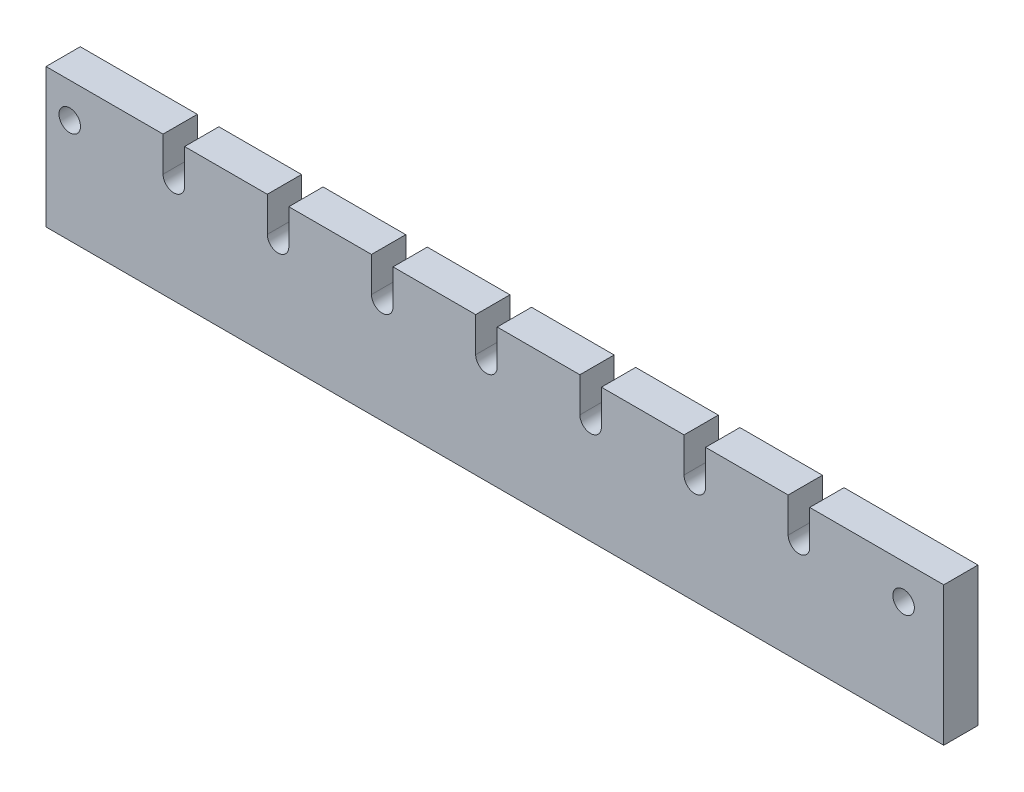
SolidWorks part; units mm, degrees
ref_plane "Front Plane" through (0, 0, 0) normal (0, 0, 1) x (1, 0, 0)
ref_plane "Top Plane" through (0, 0, 0) normal (0, 1, 0) x (1, 0, 0)
ref_plane "Right Plane" through (0, 0, 0) normal (1, 0, 0) x (0, 0, -1)
other "Configuration Table"
sketch "Sketch1" plane through (0, 0, 0) normal (0, 0, 1) x (1, 0, 0)
  line L0 (-96.35, -6.35) -> (96.35, -6.35) construction
  line L5 (-14.5354, -6.35) -> (-92.05, -6.35)
  line L6 (-14.5354, -6.35) -> (-14.5354, 5.65)
  line L7 (-14.5354, 5.65) -> (-92.05, 5.65)
  line L8 (-92.05, -6.35) -> (-92.05, 5.65)
  line L9 (-96.35, -0.35) -> (-87.75, -0.35) construction
  line L12 (-87.75, -0.35) -> (-87.75, 2.65) construction
  line L15 (96.35, -0.35) -> (-96.35, -0.35) construction
  point P8 (-92.05, -0.35)
  dimension "D1" = 14.5354
  dimension "D2" = 6
extrude "Boss-Extrude1" add sketch "Sketch1" along normal mid plane 2.9591
sketch "Sketch3" plane through (0, 0, -1.4796) normal (0, 0, -1) x (-1, 0, 0)
  line L0 (26.1081, 2.65) -> (26.1081, 5.65)
  line L1 (14.5354, 5.65) -> (92.05, 5.65) construction
  line L2 (26.1081, 5.65) -> (27.9674, 5.65)
  line L3 (27.9674, 5.65) -> (27.9674, 2.65)
  line L4 (35.0987, 2.65) -> (35.0987, 5.65)
  line L5 (35.0987, 5.65) -> (36.958, 5.65)
  line L6 (36.958, 5.65) -> (36.958, 2.65)
  line L7 (44.0931, 2.65) -> (44.0931, 5.65)
  line L8 (44.0931, 5.65) -> (45.9523, 5.65)
  line L9 (45.9523, 5.65) -> (45.9523, 2.65)
  line L10 (53.0893, 2.65) -> (53.0893, 5.65)
  line L11 (53.0893, 5.65) -> (54.9486, 5.65)
  line L12 (54.9486, 5.65) -> (54.9486, 2.65)
  line L13 (62.0866, 2.65) -> (62.0866, 5.65)
  line L14 (62.0866, 5.65) -> (63.9459, 5.65)
  line L15 (63.9459, 5.65) -> (63.9459, 2.65)
  line L16 (71.0846, 2.65) -> (71.0846, 5.65)
  line L17 (71.0846, 5.65) -> (72.9438, 5.65)
  line L18 (72.9438, 5.65) -> (72.9438, 2.65)
  line L19 (80.083, 2.65) -> (80.083, 5.65)
  line L20 (80.083, 5.65) -> (81.9423, 5.65)
  line L21 (81.9423, 5.65) -> (81.9423, 2.65)
  circle A0 centre (18, 2.65) radius 0.9296
  arc A1 (26.1081, 2.65) -> (27.9674, 2.65) centre (27.0378, 2.65) ccw
  arc A2 (35.0987, 2.65) -> (36.958, 2.65) centre (36.0284, 2.65) ccw
  arc A3 (44.0931, 2.65) -> (45.9523, 2.65) centre (45.0227, 2.65) ccw
  arc A4 (53.0893, 2.65) -> (54.9486, 2.65) centre (54.0189, 2.65) ccw
  arc A5 (62.0866, 2.65) -> (63.9459, 2.65) centre (63.0162, 2.65) ccw
  arc A6 (71.0846, 2.65) -> (72.9438, 2.65) centre (72.0142, 2.65) ccw
  arc A7 (80.083, 2.65) -> (81.9423, 2.65) centre (81.0126, 2.65) ccw
  circle A8 centre (90, 2.65) radius 0.9296
  dimension "D1" = 1.8593
extrude "Cut-Extrude1" cut sketch "Sketch3" against normal through all both and the other way through all
sketch "Sketch4" [suppressed] plane through (0, 0, -1.4796) normal (0, 0, -1) x (-1, 0, 0)
  line L25 (88.3315, 2.65) -> (88.3315, 5.65)
  line L26 (14.5354, 5.65) -> (92.05, 5.65) construction
  line L27 (88.3315, 5.65) -> (90.1908, 5.65)
  line L28 (90.1908, 5.65) -> (90.1908, 2.65)
  line L29 (81.1921, 2.65) -> (81.1921, 5.65)
  line L30 (81.1921, 5.65) -> (79.3328, 5.65)
  line L31 (79.3328, 5.65) -> (79.3328, 2.65)
  line L32 (72.1938, 2.65) -> (72.1938, 5.65)
  line L33 (72.1938, 5.65) -> (70.3345, 5.65)
  line L34 (70.3345, 5.65) -> (70.3345, 2.65)
  line L35 (63.1959, 2.65) -> (63.1959, 5.65)
  line L36 (63.1959, 5.65) -> (61.3366, 5.65)
  line L37 (61.3366, 5.65) -> (61.3366, 2.65)
  line L38 (54.1987, 2.65) -> (54.1987, 5.65)
  line L39 (54.1987, 5.65) -> (52.3394, 5.65)
  line L40 (52.3394, 5.65) -> (52.3394, 2.65)
  line L41 (45.2026, 2.65) -> (45.2026, 5.65)
  line L42 (45.2026, 5.65) -> (43.3433, 5.65)
  line L43 (43.3433, 5.65) -> (43.3433, 2.65)
  line L44 (36.2085, 2.65) -> (36.2085, 5.65)
  line L45 (36.2085, 5.65) -> (34.3493, 5.65)
  line L46 (34.3493, 5.65) -> (34.3493, 2.65)
  line L47 (27.2185, 2.65) -> (27.2185, 5.65)
  line L48 (27.2185, 5.65) -> (25.3592, 5.65)
  line L49 (25.3592, 5.65) -> (25.3592, 2.65)
  arc A2 (70.3345, 2.65) -> (72.1938, 2.65) centre (71.2641, 2.65) ccw
  arc A4 (61.3366, 2.65) -> (63.1959, 2.65) centre (62.2662, 2.65) ccw
  arc A6 (52.3394, 2.65) -> (54.1987, 2.65) centre (53.269, 2.65) ccw
  arc A8 (43.3433, 2.65) -> (45.2026, 2.65) centre (44.273, 2.65) ccw
  arc A10 (34.3493, 2.65) -> (36.2085, 2.65) centre (35.2789, 2.65) ccw
  arc A12 (25.3592, 2.65) -> (27.2185, 2.65) centre (26.2888, 2.65) ccw
  arc A16 (88.3315, 2.65) -> (90.1908, 2.65) centre (89.2612, 2.65) ccw
  arc A18 (79.3328, 2.65) -> (81.1921, 2.65) centre (80.2625, 2.65) ccw
  dimension "D1" = 1.8593
extrude "Cut-Extrude2" [suppressed] cut sketch "Sketch4" against normal through all both and the other way through all
sketch "Sketch5" [suppressed] plane through (0, 0, -1.4796) normal (0, 0, -1) x (-1, 0, 0)
  line L0 (-84.012, 2.65) -> (88.5114, 2.65) construction
  line L1 (24.6104, 2.65) -> (24.6104, 5.65)
  line L2 (14.5354, 5.65) -> (92.05, 5.65) construction
  line L3 (24.6104, 5.65) -> (26.4697, 5.65)
  line L4 (26.4697, 5.65) -> (26.4697, 2.65)
  line L5 (33.6, 2.65) -> (33.6, 5.65)
  line L6 (33.6, 5.65) -> (35.4593, 5.65)
  line L7 (35.4593, 5.65) -> (35.4593, 2.65)
  line L8 (42.5938, 2.65) -> (42.5938, 5.65)
  line L9 (42.5938, 5.65) -> (44.4531, 5.65)
  line L10 (44.4531, 5.65) -> (44.4531, 2.65)
  line L11 (51.5898, 2.65) -> (51.5898, 5.65)
  line L12 (51.5898, 5.65) -> (53.4491, 5.65)
  line L13 (53.4491, 5.65) -> (53.4491, 2.65)
  line L14 (60.5869, 2.65) -> (60.5869, 5.65)
  line L15 (60.5869, 5.65) -> (62.4462, 5.65)
  line L16 (62.4462, 5.65) -> (62.4462, 2.65)
  line L17 (69.5848, 2.65) -> (69.5848, 5.65)
  line L18 (69.5848, 5.65) -> (71.444, 5.65)
  line L19 (71.444, 5.65) -> (71.444, 2.65)
  line L20 (78.5831, 2.65) -> (78.5831, 5.65)
  line L21 (78.5831, 5.65) -> (80.4424, 5.65)
  line L22 (80.4424, 5.65) -> (80.4424, 2.65)
  line L23 (87.5817, 2.65) -> (87.5817, 5.65)
  line L24 (87.5817, 5.65) -> (89.441, 5.65)
  line L25 (89.441, 5.65) -> (89.441, 2.65)
  arc A2 (69.5848, 2.65) -> (71.444, 2.65) centre (70.5144, 2.65) ccw
  arc A4 (60.5869, 2.65) -> (62.4462, 2.65) centre (61.5166, 2.65) ccw
  arc A6 (51.5898, 2.65) -> (53.4491, 2.65) centre (52.5194, 2.65) ccw
  arc A8 (42.5938, 2.65) -> (44.4531, 2.65) centre (43.5235, 2.65) ccw
  arc A10 (33.6, 2.65) -> (35.4593, 2.65) centre (34.5296, 2.65) ccw
  arc A12 (24.6104, 2.65) -> (26.4697, 2.65) centre (25.5401, 2.65) ccw
  arc A16 (87.5817, 2.65) -> (89.441, 2.65) centre (88.5114, 2.65) ccw
  arc A18 (78.5831, 2.65) -> (80.4424, 2.65) centre (79.5127, 2.65) ccw
  dimension "D1" = 1.8593
extrude "Cut-Extrude3" [suppressed] cut sketch "Sketch5" against normal through all both and the other way through all
sketch "Sketch7" [suppressed] plane through (0, 0, -1.4796) normal (0, 0, -1) x (-1, 0, 0)
  line L0 (-83.2623, 2.65) -> (87.7617, 2.65) construction
  line L1 (23.8616, 2.65) -> (23.8616, 5.65)
  line L2 (14.5354, 5.65) -> (92.05, 5.65) construction
  line L3 (23.8616, 5.65) -> (25.7208, 5.65)
  line L4 (25.7208, 5.65) -> (25.7208, 2.65)
  line L5 (32.8506, 2.65) -> (32.8506, 5.65)
  line L6 (32.8506, 5.65) -> (34.7099, 5.65)
  line L7 (34.7099, 5.65) -> (34.7099, 2.65)
  line L8 (41.8443, 2.65) -> (41.8443, 5.65)
  line L9 (41.8443, 5.65) -> (43.7035, 5.65)
  line L10 (43.7035, 5.65) -> (43.7035, 2.65)
  line L11 (50.8401, 2.65) -> (50.8401, 5.65)
  line L12 (50.8401, 5.65) -> (52.6994, 5.65)
  line L13 (52.6994, 5.65) -> (52.6994, 2.65)
  line L14 (59.8372, 2.65) -> (59.8372, 5.65)
  line L15 (59.8372, 5.65) -> (61.6965, 5.65)
  line L16 (61.6965, 5.65) -> (61.6965, 2.65)
  line L17 (68.835, 2.65) -> (68.835, 5.65)
  line L18 (68.835, 5.65) -> (70.6943, 5.65)
  line L19 (70.6943, 5.65) -> (70.6943, 2.65)
  line L20 (77.8333, 2.65) -> (77.8333, 5.65)
  line L21 (77.8333, 5.65) -> (79.6926, 5.65)
  line L22 (79.6926, 5.65) -> (79.6926, 2.65)
  line L23 (86.832, 2.65) -> (86.832, 5.65)
  line L24 (86.832, 5.65) -> (88.6913, 5.65)
  line L25 (88.6913, 5.65) -> (88.6913, 2.65)
  arc A2 (68.835, 2.65) -> (70.6943, 2.65) centre (69.7646, 2.65) ccw
  arc A4 (59.8372, 2.65) -> (61.6965, 2.65) centre (60.7668, 2.65) ccw
  arc A6 (50.8401, 2.65) -> (52.6994, 2.65) centre (51.7697, 2.65) ccw
  arc A8 (41.8443, 2.65) -> (43.7035, 2.65) centre (42.7739, 2.65) ccw
  arc A10 (32.8506, 2.65) -> (34.7099, 2.65) centre (33.7802, 2.65) ccw
  arc A12 (23.8616, 2.65) -> (25.7208, 2.65) centre (24.7912, 2.65) ccw
  arc A16 (86.832, 2.65) -> (88.6913, 2.65) centre (87.7616, 2.65) ccw
  arc A18 (77.8333, 2.65) -> (79.6926, 2.65) centre (78.763, 2.65) ccw
  dimension "D1" = 1.8593
extrude "Cut-Extrude4" [suppressed] cut sketch "Sketch7" against normal through all
sketch "Sketch8" [suppressed] plane through (0, 0, -1.4796) normal (0, 0, -1) x (-1, 0, 0)
  line L0 (23.1128, 2.65) -> (23.1128, 5.65)
  line L1 (14.5354, 5.65) -> (92.05, 5.65) construction
  line L2 (23.1128, 5.65) -> (24.9721, 5.65)
  line L3 (24.9721, 5.65) -> (24.9721, 2.65)
  line L4 (32.1012, 2.65) -> (32.1012, 5.65)
  line L5 (32.1012, 5.65) -> (33.9605, 5.65)
  line L6 (33.9605, 5.65) -> (33.9605, 2.65)
  line L7 (41.0946, 2.65) -> (41.0946, 5.65)
  line L8 (41.0946, 5.65) -> (42.9539, 5.65)
  line L9 (42.9539, 5.65) -> (42.9539, 2.65)
  line L10 (50.0902, 2.65) -> (50.0902, 5.65)
  line L11 (50.0902, 5.65) -> (51.9495, 5.65)
  line L12 (51.9495, 5.65) -> (51.9495, 2.65)
  line L13 (59.0872, 2.65) -> (59.0872, 5.65)
  line L14 (59.0872, 5.65) -> (60.9465, 5.65)
  line L15 (60.9465, 5.65) -> (60.9465, 2.65)
  line L16 (68.0849, 2.65) -> (68.0849, 5.65)
  line L17 (68.0849, 5.65) -> (69.9442, 5.65)
  line L18 (69.9442, 5.65) -> (69.9442, 2.65)
  line L19 (77.0832, 2.65) -> (77.0832, 5.65)
  line L20 (77.0832, 5.65) -> (78.9425, 5.65)
  line L21 (78.9425, 5.65) -> (78.9425, 2.65)
  line L22 (86.0818, 2.65) -> (86.0818, 5.65)
  line L23 (86.0818, 5.65) -> (87.9411, 5.65)
  line L24 (87.9411, 5.65) -> (87.9411, 2.65)
  arc A2 (41.0946, 2.65) -> (42.9539, 2.65) centre (42.0242, 2.65) ccw
  arc A4 (50.0902, 2.65) -> (51.9495, 2.65) centre (51.0199, 2.65) ccw
  arc A6 (59.0872, 2.65) -> (60.9465, 2.65) centre (60.0168, 2.65) ccw
  arc A8 (68.0849, 2.65) -> (69.9442, 2.65) centre (69.0146, 2.65) ccw
  arc A10 (77.0832, 2.65) -> (78.9425, 2.65) centre (78.0128, 2.65) ccw
  arc A12 (86.0818, 2.65) -> (87.9411, 2.65) centre (87.0115, 2.65) ccw
  arc A14 (23.1128, 2.65) -> (24.9721, 2.65) centre (24.0425, 2.65) ccw
  arc A16 (32.1012, 2.65) -> (33.9605, 2.65) centre (33.0309, 2.65) ccw
  dimension "D1" = 1.8593
extrude "Cut-Extrude5" [suppressed] cut sketch "Sketch8" against normal through all
sketch "Sketch9" [suppressed] plane through (0, 0, -1.4796) normal (0, 0, -1) x (-1, 0, 0)
  line L0 (22.3643, 2.65) -> (22.3643, 5.65)
  line L1 (14.5354, 5.65) -> (92.05, 5.65) construction
  line L2 (22.3643, 5.65) -> (24.2236, 5.65)
  line L3 (24.2236, 5.65) -> (24.2236, 2.65)
  line L4 (31.3521, 2.65) -> (31.3521, 5.65)
  line L5 (31.3521, 5.65) -> (33.2113, 5.65)
  line L6 (33.2113, 5.65) -> (33.2113, 2.65)
  line L7 (40.3451, 2.65) -> (40.3451, 5.65)
  line L8 (40.3451, 5.65) -> (42.2044, 5.65)
  line L9 (42.2044, 5.65) -> (42.2044, 2.65)
  line L10 (49.3407, 2.65) -> (49.3407, 5.65)
  line L11 (49.3407, 5.65) -> (51.1999, 5.65)
  line L12 (51.1999, 5.65) -> (51.1999, 2.65)
  line L13 (58.3375, 2.65) -> (58.3375, 5.65)
  line L14 (58.3375, 5.65) -> (60.1968, 5.65)
  line L15 (60.1968, 5.65) -> (60.1968, 2.65)
  line L16 (67.3352, 2.65) -> (67.3352, 5.65)
  line L17 (67.3352, 5.65) -> (69.1945, 5.65)
  line L18 (69.1945, 5.65) -> (69.1945, 2.65)
  line L19 (76.3335, 2.65) -> (76.3335, 5.65)
  line L20 (76.3335, 5.65) -> (78.1927, 5.65)
  line L21 (78.1927, 5.65) -> (78.1927, 2.65)
  line L22 (85.3321, 2.65) -> (85.3321, 5.65)
  line L23 (85.3321, 5.65) -> (87.1913, 5.65)
  line L24 (87.1913, 5.65) -> (87.1913, 2.65)
  arc A2 (67.3352, 2.65) -> (69.1945, 2.65) centre (68.2649, 2.65) ccw
  arc A4 (58.3375, 2.65) -> (60.1968, 2.65) centre (59.2672, 2.65) ccw
  arc A6 (49.3407, 2.65) -> (51.1999, 2.65) centre (50.2703, 2.65) ccw
  arc A8 (40.3451, 2.65) -> (42.2044, 2.65) centre (41.2748, 2.65) ccw
  arc A10 (31.3521, 2.65) -> (33.2113, 2.65) centre (32.2817, 2.65) ccw
  arc A12 (22.3643, 2.65) -> (24.2236, 2.65) centre (23.2939, 2.65) ccw
  arc A14 (85.3321, 2.65) -> (87.1913, 2.65) centre (86.2617, 2.65) ccw
  arc A16 (76.3335, 2.65) -> (78.1927, 2.65) centre (77.2631, 2.65) ccw
  dimension "D1" = 1.8593
extrude "Cut-Extrude6" [suppressed] cut sketch "Sketch9" against normal through all
sketch "Sketch10" [suppressed] plane through (0, 0, -1.4796) normal (0, 0, -1) x (-1, 0, 0)
  line L0 (21.6157, 2.65) -> (21.6157, 5.65)
  line L1 (14.5354, 5.65) -> (92.05, 5.65) construction
  line L2 (21.6157, 5.65) -> (23.4749, 5.65)
  line L3 (23.4749, 5.65) -> (23.4749, 2.65)
  line L4 (30.6028, 2.65) -> (30.6028, 5.65)
  line L5 (30.6028, 5.65) -> (32.462, 5.65)
  line L6 (32.462, 5.65) -> (32.462, 2.65)
  line L7 (39.5956, 2.65) -> (39.5956, 5.65)
  line L8 (39.5956, 5.65) -> (41.4549, 5.65)
  line L9 (41.4549, 5.65) -> (41.4549, 2.65)
  line L10 (48.591, 2.65) -> (48.591, 5.65)
  line L11 (48.591, 5.65) -> (50.4503, 5.65)
  line L12 (50.4503, 5.65) -> (50.4503, 2.65)
  line L13 (57.5878, 2.65) -> (57.5878, 5.65)
  line L14 (57.5878, 5.65) -> (59.4471, 5.65)
  line L15 (59.4471, 5.65) -> (59.4471, 2.65)
  line L16 (66.5855, 2.65) -> (66.5855, 5.65)
  line L17 (66.5855, 5.65) -> (68.4448, 5.65)
  line L18 (68.4448, 5.65) -> (68.4448, 2.65)
  line L19 (75.5837, 2.65) -> (75.5837, 5.65)
  line L20 (75.5837, 5.65) -> (77.443, 5.65)
  line L21 (77.443, 5.65) -> (77.443, 2.65)
  line L22 (84.5823, 2.65) -> (84.5823, 5.65)
  line L23 (84.5823, 5.65) -> (86.4416, 5.65)
  line L24 (86.4416, 5.65) -> (86.4416, 2.65)
  arc A2 (66.5855, 2.65) -> (68.4448, 2.65) centre (67.5151, 2.65) ccw
  arc A4 (57.5878, 2.65) -> (59.4471, 2.65) centre (58.5175, 2.65) ccw
  arc A6 (48.591, 2.65) -> (50.4503, 2.65) centre (49.5206, 2.65) ccw
  arc A8 (39.5956, 2.65) -> (41.4549, 2.65) centre (40.5252, 2.65) ccw
  arc A10 (30.6028, 2.65) -> (32.462, 2.65) centre (31.5324, 2.65) ccw
  arc A12 (21.6157, 2.65) -> (23.4749, 2.65) centre (22.5453, 2.65) ccw
  arc A14 (84.5823, 2.65) -> (86.4416, 2.65) centre (85.512, 2.65) ccw
  arc A16 (75.5837, 2.65) -> (77.443, 2.65) centre (76.5134, 2.65) ccw
  dimension "D1" = 1.8593
extrude "Cut-Extrude7" [suppressed] cut sketch "Sketch10" against normal through all
sketch "Sketch11" [suppressed] plane through (0, 0, -1.4796) normal (0, 0, -1) x (-1, 0, 0)
  line L0 (20.8672, 2.65) -> (20.8672, 5.65)
  line L1 (14.5354, 5.65) -> (92.05, 5.65) construction
  line L2 (20.8672, 5.65) -> (22.7265, 5.65)
  line L3 (22.7265, 5.65) -> (22.7265, 2.65)
  line L4 (29.8535, 2.65) -> (29.8535, 5.65)
  line L5 (29.8535, 5.65) -> (31.7128, 5.65)
  line L6 (31.7128, 5.65) -> (31.7128, 2.65)
  line L7 (38.846, 2.65) -> (38.846, 5.65)
  line L8 (38.846, 5.65) -> (40.7052, 5.65)
  line L9 (40.7052, 5.65) -> (40.7052, 2.65)
  line L10 (47.8412, 2.65) -> (47.8412, 5.65)
  line L11 (47.8412, 5.65) -> (49.7005, 5.65)
  line L12 (49.7005, 5.65) -> (49.7005, 2.65)
  line L13 (56.8379, 2.65) -> (56.8379, 5.65)
  line L14 (56.8379, 5.65) -> (58.6972, 5.65)
  line L15 (58.6972, 5.65) -> (58.6972, 2.65)
  line L16 (65.8355, 2.65) -> (65.8355, 5.65)
  line L17 (65.8355, 5.65) -> (67.6947, 5.65)
  line L18 (67.6947, 5.65) -> (67.6947, 2.65)
  line L19 (74.8336, 2.65) -> (74.8336, 5.65)
  line L20 (74.8336, 5.65) -> (76.6929, 5.65)
  line L21 (76.6929, 5.65) -> (76.6929, 2.65)
  line L22 (83.8321, 2.65) -> (83.8321, 5.65)
  line L23 (83.8321, 5.65) -> (85.6914, 5.65)
  line L24 (85.6914, 5.65) -> (85.6914, 2.65)
  arc A2 (38.846, 2.65) -> (40.7052, 2.65) centre (39.7756, 2.65) ccw
  arc A4 (47.8412, 2.65) -> (49.7005, 2.65) centre (48.7708, 2.65) ccw
  arc A6 (56.8379, 2.65) -> (58.6972, 2.65) centre (57.7675, 2.65) ccw
  arc A8 (65.8355, 2.65) -> (67.6947, 2.65) centre (66.7651, 2.65) ccw
  arc A10 (74.8336, 2.65) -> (76.6929, 2.65) centre (75.7632, 2.65) ccw
  arc A12 (83.8321, 2.65) -> (85.6914, 2.65) centre (84.7618, 2.65) ccw
  arc A14 (20.8672, 2.65) -> (22.7265, 2.65) centre (21.7969, 2.65) ccw
  arc A16 (29.8535, 2.65) -> (31.7128, 2.65) centre (30.7831, 2.65) ccw
  dimension "D1" = 1.8593
extrude "Cut-Extrude8" [suppressed] cut sketch "Sketch11" against normal through all
sketch "Sketch12" [suppressed] plane through (0, 0, -1.4796) normal (0, 0, -1) x (-1, 0, 0)
  line L0 (20.1189, 2.65) -> (20.1189, 5.65)
  line L1 (14.5354, 5.65) -> (92.05, 5.65) construction
  line L2 (20.1189, 5.65) -> (21.9782, 5.65)
  line L3 (21.9782, 5.65) -> (21.9782, 2.65)
  line L4 (29.1044, 2.65) -> (29.1044, 5.65)
  line L5 (29.1044, 5.65) -> (30.9637, 5.65)
  line L6 (30.9637, 5.65) -> (30.9637, 2.65)
  line L7 (38.0966, 2.65) -> (38.0966, 5.65)
  line L8 (38.0966, 5.65) -> (39.9558, 5.65)
  line L9 (39.9558, 5.65) -> (39.9558, 2.65)
  line L10 (47.0916, 2.65) -> (47.0916, 5.65)
  line L11 (47.0916, 5.65) -> (48.9509, 5.65)
  line L12 (48.9509, 5.65) -> (48.9509, 2.65)
  line L13 (56.0882, 2.65) -> (56.0882, 5.65)
  line L14 (56.0882, 5.65) -> (57.9475, 5.65)
  line L15 (57.9475, 5.65) -> (57.9475, 2.65)
  line L16 (65.0858, 2.65) -> (65.0858, 5.65)
  line L17 (65.0858, 5.65) -> (66.945, 5.65)
  line L18 (66.945, 5.65) -> (66.945, 2.65)
  line L19 (74.0839, 2.65) -> (74.0839, 5.65)
  line L20 (74.0839, 5.65) -> (75.9432, 5.65)
  line L21 (75.9432, 5.65) -> (75.9432, 2.65)
  line L22 (84.9417, 2.65) -> (84.9417, 5.65)
  line L23 (84.9417, 5.65) -> (83.0824, 5.65)
  line L24 (83.0824, 5.65) -> (83.0824, 2.65)
  arc A2 (65.0858, 2.65) -> (66.945, 2.65) centre (66.0154, 2.65) ccw
  arc A4 (56.0882, 2.65) -> (57.9475, 2.65) centre (57.0179, 2.65) ccw
  arc A6 (47.0916, 2.65) -> (48.9509, 2.65) centre (48.0213, 2.65) ccw
  arc A8 (38.0966, 2.65) -> (39.9558, 2.65) centre (39.0262, 2.65) ccw
  arc A10 (29.1044, 2.65) -> (30.9637, 2.65) centre (30.0341, 2.65) ccw
  arc A12 (20.1189, 2.65) -> (21.9782, 2.65) centre (21.0486, 2.65) ccw
  arc A14 (83.0824, 2.65) -> (84.9417, 2.65) centre (84.012, 2.65) ccw
  arc A16 (74.0839, 2.65) -> (75.9432, 2.65) centre (75.0135, 2.65) ccw
  dimension "D1" = 1.8593
extrude "Cut-Extrude9" [suppressed] cut sketch "Sketch12" against normal through all
sketch "Sketch13" [suppressed] plane through (0, 0, -1.4796) normal (0, 0, -1) x (-1, 0, 0)
  line L0 (19.3707, 2.65) -> (19.3707, 5.65)
  line L1 (14.5354, 5.65) -> (92.05, 5.65) construction
  line L2 (19.3707, 5.65) -> (21.2299, 5.65)
  line L3 (21.2299, 5.65) -> (21.2299, 2.65)
  line L4 (28.3552, 2.65) -> (28.3552, 5.65)
  line L5 (28.3552, 5.65) -> (30.2145, 5.65)
  line L6 (30.2145, 5.65) -> (30.2145, 2.65)
  line L7 (37.3471, 2.65) -> (37.3471, 5.65)
  line L8 (37.3471, 5.65) -> (39.2063, 5.65)
  line L9 (39.2063, 5.65) -> (39.2063, 2.65)
  line L10 (46.342, 2.65) -> (46.342, 5.65)
  line L11 (46.342, 5.65) -> (48.2013, 5.65)
  line L12 (48.2013, 5.65) -> (48.2013, 2.65)
  line L13 (55.3385, 2.65) -> (55.3385, 5.65)
  line L14 (55.3385, 5.65) -> (57.1978, 5.65)
  line L15 (57.1978, 5.65) -> (57.1978, 2.65)
  line L16 (64.336, 2.65) -> (64.336, 5.65)
  line L17 (64.336, 5.65) -> (66.1953, 5.65)
  line L18 (66.1953, 5.65) -> (66.1953, 2.65)
  line L19 (73.3341, 2.65) -> (73.3341, 5.65)
  line L20 (73.3341, 5.65) -> (75.1934, 5.65)
  line L21 (75.1934, 5.65) -> (75.1934, 2.65)
  line L22 (82.3326, 2.65) -> (82.3326, 5.65)
  line L23 (82.3326, 5.65) -> (84.1919, 5.65)
  line L24 (84.1919, 5.65) -> (84.1919, 2.65)
  arc A2 (37.3471, 2.65) -> (39.2063, 2.65) centre (38.2767, 2.65) ccw
  arc A4 (46.342, 2.65) -> (48.2013, 2.65) centre (47.2716, 2.65) ccw
  arc A6 (55.3385, 2.65) -> (57.1978, 2.65) centre (56.2682, 2.65) ccw
  arc A8 (64.336, 2.65) -> (66.1953, 2.65) centre (65.2657, 2.65) ccw
  arc A10 (73.3341, 2.65) -> (75.1934, 2.65) centre (74.2638, 2.65) ccw
  arc A12 (82.3326, 2.65) -> (84.1919, 2.65) centre (83.2623, 2.65) ccw
  arc A14 (19.3707, 2.65) -> (21.2299, 2.65) centre (20.3003, 2.65) ccw
  arc A16 (28.3552, 2.65) -> (30.2145, 2.65) centre (29.2849, 2.65) ccw
  dimension "D1" = 1.8593
extrude "Cut-Extrude10" [suppressed] cut sketch "Sketch13" against normal through all
sketch "Sketch14" [suppressed] plane through (0, 0, -1.4796) normal (0, 0, -1) x (-1, 0, 0)
  line L0 (18.6226, 2.65) -> (18.6226, 5.65)
  line L1 (14.5354, 5.65) -> (92.05, 5.65) construction
  line L2 (18.6226, 5.65) -> (20.4819, 5.65)
  line L3 (20.4819, 5.65) -> (20.4819, 2.65)
  line L4 (27.6061, 2.65) -> (27.6061, 5.65)
  line L5 (27.6061, 5.65) -> (29.4654, 5.65)
  line L6 (29.4654, 5.65) -> (29.4654, 2.65)
  line L7 (36.5975, 2.65) -> (36.5975, 5.65)
  line L8 (36.5975, 5.65) -> (38.4568, 5.65)
  line L9 (38.4568, 5.65) -> (38.4568, 2.65)
  line L10 (45.5922, 2.65) -> (45.5922, 5.65)
  line L11 (45.5922, 5.65) -> (47.4515, 5.65)
  line L12 (47.4515, 5.65) -> (47.4515, 2.65)
  line L13 (54.5886, 2.65) -> (54.5886, 5.65)
  line L14 (54.5886, 5.65) -> (56.4479, 5.65)
  line L15 (56.4479, 5.65) -> (56.4479, 2.65)
  line L16 (63.586, 2.65) -> (63.586, 5.65)
  line L17 (63.586, 5.65) -> (65.4453, 5.65)
  line L18 (65.4453, 5.65) -> (65.4453, 2.65)
  line L19 (72.584, 2.65) -> (72.584, 5.65)
  line L20 (72.584, 5.65) -> (74.4433, 5.65)
  line L21 (74.4433, 5.65) -> (74.4433, 2.65)
  line L22 (81.5825, 2.65) -> (81.5825, 5.65)
  line L23 (81.5825, 5.65) -> (83.4418, 5.65)
  line L24 (83.4418, 5.65) -> (83.4418, 2.65)
  arc A2 (63.586, 2.65) -> (65.4453, 2.65) centre (64.5156, 2.65) ccw
  arc A4 (54.5886, 2.65) -> (56.4479, 2.65) centre (55.5182, 2.65) ccw
  arc A6 (45.5922, 2.65) -> (47.4515, 2.65) centre (46.5218, 2.65) ccw
  arc A8 (36.5975, 2.65) -> (38.4568, 2.65) centre (37.5271, 2.65) ccw
  arc A10 (27.6061, 2.65) -> (29.4654, 2.65) centre (28.5358, 2.65) ccw
  arc A12 (18.6226, 2.65) -> (20.4819, 2.65) centre (19.5522, 2.65) ccw
  arc A14 (81.5825, 2.65) -> (83.4418, 2.65) centre (82.5121, 2.65) ccw
  arc A16 (72.584, 2.65) -> (74.4433, 2.65) centre (73.5137, 2.65) ccw
  dimension "D1" = 1.8593
extrude "Cut-Extrude11" [suppressed] cut sketch "Sketch14" against normal through all
sketch "Sketch15" [suppressed] plane through (0, 0, -1.4796) normal (0, 0, -1) x (-1, 0, 0)
  line L25 (17.8747, 2.65) -> (17.8747, 5.65)
  line L26 (14.5354, 5.65) -> (92.05, 5.65) construction
  line L27 (17.8747, 5.65) -> (19.734, 5.65)
  line L28 (19.734, 5.65) -> (19.734, 2.65)
  line L29 (26.8572, 2.65) -> (26.8572, 5.65)
  line L30 (26.8572, 5.65) -> (28.7165, 5.65)
  line L31 (28.7165, 5.65) -> (28.7165, 2.65)
  line L32 (35.8482, 2.65) -> (35.8482, 5.65)
  line L33 (35.8482, 5.65) -> (37.7075, 5.65)
  line L34 (37.7075, 5.65) -> (37.7075, 2.65)
  line L35 (44.8427, 2.65) -> (44.8427, 5.65)
  line L36 (44.8427, 5.65) -> (46.702, 5.65)
  line L37 (46.702, 5.65) -> (46.702, 2.65)
  line L38 (53.839, 2.65) -> (53.839, 5.65)
  line L39 (53.839, 5.65) -> (55.6983, 5.65)
  line L40 (55.6983, 5.65) -> (55.6983, 2.65)
  line L41 (62.8363, 2.65) -> (62.8363, 5.65)
  line L42 (62.8363, 5.65) -> (64.6956, 5.65)
  line L43 (64.6956, 5.65) -> (64.6956, 2.65)
  line L44 (71.8343, 2.65) -> (71.8343, 5.65)
  line L45 (71.8343, 5.65) -> (73.6936, 5.65)
  line L46 (73.6936, 5.65) -> (73.6936, 2.65)
  line L47 (80.8327, 2.65) -> (80.8327, 5.65)
  line L48 (80.8327, 5.65) -> (82.692, 5.65)
  line L49 (82.692, 5.65) -> (82.692, 2.65)
  arc A2 (35.8482, 2.65) -> (37.7075, 2.65) centre (36.7778, 2.65) ccw
  arc A4 (44.8427, 2.65) -> (46.702, 2.65) centre (45.7723, 2.65) ccw
  arc A6 (53.839, 2.65) -> (55.6983, 2.65) centre (54.7686, 2.65) ccw
  arc A8 (62.8363, 2.65) -> (64.6956, 2.65) centre (63.766, 2.65) ccw
  arc A10 (71.8343, 2.65) -> (73.6936, 2.65) centre (72.7639, 2.65) ccw
  arc A12 (80.8327, 2.65) -> (82.692, 2.65) centre (81.7624, 2.65) ccw
  arc A14 (17.8747, 2.65) -> (19.734, 2.65) centre (18.8044, 2.65) ccw
  arc A16 (26.8572, 2.65) -> (28.7165, 2.65) centre (27.7868, 2.65) ccw
  dimension "D1" = 1.8593
extrude "Cut-Extrude12" [suppressed] cut sketch "Sketch15" against normal through all
equation "\"wire gauge\"= 14"
equation "\"wire diameter\"= 0.005 * 92 ^ ( ( 36 - \"wire gauge\" ) / 39 ) * 1in"
equation "\"wire diameter with insulation\"= 0.0682 * 1in"
equation "\"insulation thickness\"= ( \"wire diameter with insulation\" - \"wire diameter\" ) / 2 * 1in"
equation "\"bend radius\"= \"wire diameter with insulation\" * 3"
equation "\"inner diameter\"= 36 * 1mm"
equation "\"outer diameter\"= 180 * 1mm"
equation "\"turns\"= 8"
equation "\"pitch\"= ( \"outer diameter\" - \"inner diameter\" ) / \"turns\" / 2"
equation "\"D1@Sketch1\"=\"inner diameter\"/2-\"wire diameter with insulation\"*2"
equation "\"hole size\"= \"wire diameter with insulation\" + 0.005"
equation "\"D1@Sketch3\"=\"hole size\""
equation "\"D1@Sketch4\"=\"hole size\""
equation "\"D1@Sketch5\"=\"hole size\""
equation "\"D1@Sketch7\"=\"hole size\""
equation "\"D1@Sketch8\"=\"hole size\""
equation "\"D1@Sketch9\"=\"hole size\""
equation "\"D1@Sketch10\"=\"hole size\""
equation "\"D1@Sketch11\"=\"hole size\""
equation "\"D1@Sketch12\"=\"hole size\""
equation "\"D1@Sketch13\"=\"hole size\""
equation "\"D1@Sketch14\"=\"hole size\""
equation "\"D1@Sketch15\"=\"hole size\""
